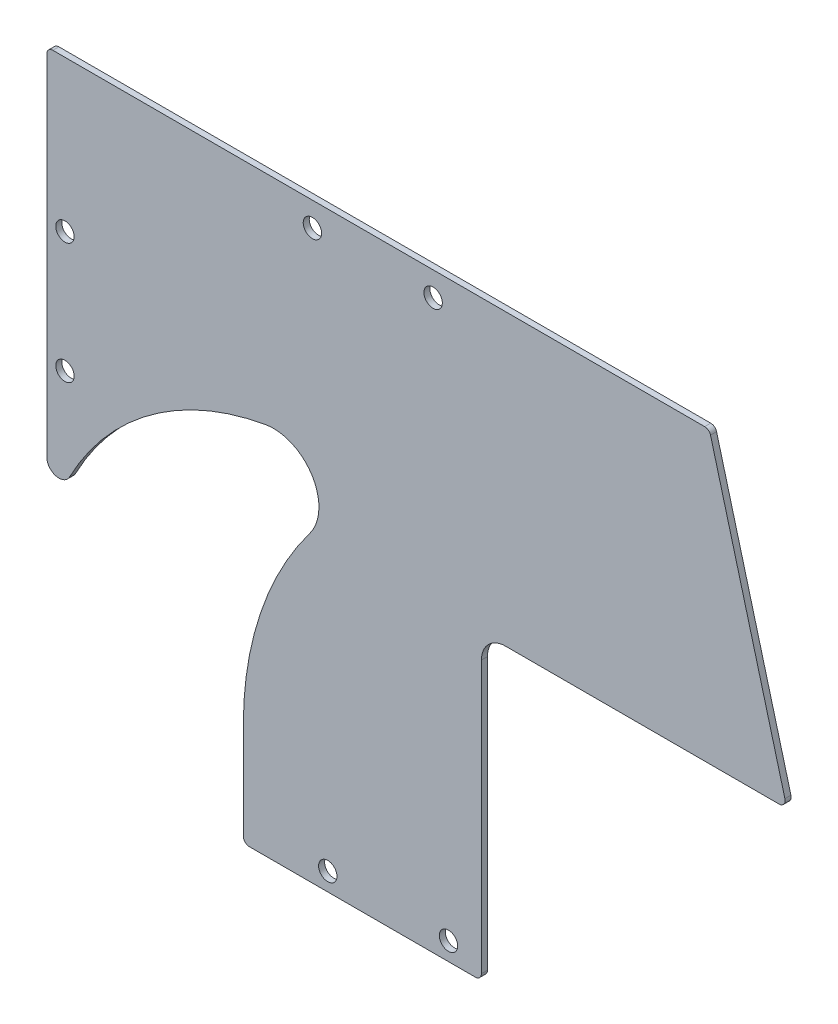
SolidWorks part; units mm, degrees
material "Thornel Mat VMA"
ref_plane "前视基准面" through (0, 0, 0) normal (0, 0, 1) x (1, 0, 0)
ref_plane "上视基准面" through (0, 0, 0) normal (0, 1, 0) x (1, 0, 0)
ref_plane "右视基准面" through (0, 0, 0) normal (1, 0, 0) x (0, 0, -1)
other "Configuration Table"
sketch "草图1" plane through (0, 0, 0) normal (0, 0, 1) x (1, 0, 0)
  line L1 (-70, -51.5) -> (70, -51.5)
  line L2 (-70, -51.5) -> (-70, 51.5)
  line L3 (-70, 51.5) -> (70, 51.5)
  line L4 (70, -51.5) -> (70, 51.5)
  line L5 (-70, -51.5) -> (70, 51.5) construction
  line L6 (-70, 51.5) -> (70, -51.5) construction
  point P0 (0, 0)
  dimension "D1" = 103
  dimension "D2" = 140
extrude "凸台-拉伸1" add sketch "草图1" along normal mid plane 1
sketch "草图2" plane through (0, 0, 0.5) normal (0, 0, 1) x (1, 0, 0)
  line L0 (58.9835, -20.2244) -> (45.4361, 30.3352) construction
  line L1 (67.3638, -51.5) -> (45.4361, 30.3352) construction
  line L2 (-70, -51.5) -> (70, -51.5) construction
  line L3 (-68.4454, -29.5) -> (-68.4454, -77.5)
  line L4 (-66.4454, -79.5) -> (-42.4454, -79.5)
  line L5 (-40.4454, -77.5) -> (-40.4454, -29.5)
  line L6 (-68.4454, -29.5) -> (-68.4454, -77.5) construction
  line L7 (-66.4454, -79.5) -> (-42.4454, -79.5) construction
  line L8 (-40.4454, -77.5) -> (-40.4454, -29.5) construction
  line L9 (-71.4454, -29.5) -> (-71.4454, -77.5)
  line L10 (6, -79.5) -> (34, -79.5)
  line L11 (35, -78.5) -> (35, -0.5)
  line L12 (34, 0.5) -> (6, 0.5)
  line L13 (5, -0.5) -> (5, -78.5)
  line L14 (6, -79.5) -> (34, -79.5) construction
  line L15 (35, -78.5) -> (35, -0.5) construction
  line L16 (34, 0.5) -> (6, 0.5) construction
  line L17 (5, -0.5) -> (5, -78.5) construction
  line L18 (-66.4454, -82.5) -> (-42.4454, -82.5)
  line L19 (-37.4454, -77.5) -> (-37.4454, -29.5)
  line L20 (6, -82.5) -> (34, -82.5)
  line L21 (38, -78.5) -> (38, -0.5)
  line L22 (34, 3.5) -> (6, 3.5)
  line L23 (2, -0.5) -> (2, -78.5)
  arc A0 (-71.4454, -77.5) -> (-66.4454, -82.5) centre (-66.4454, -77.5) ccw
  arc A1 (-42.4454, -82.5) -> (-37.4454, -77.5) centre (-42.4454, -77.5) ccw
  arc A2 (-26.4309, 3.4778) -> (-37.4454, -29.5) centre (17.4298, -29.5) ccw
  arc A3 (-26.4309, 3.4778) -> (-33.7501, 15.411) centre (-32.4454, 8) ccw
  arc A4 (34, -79.5) -> (35, -78.5) centre (34, -78.5) ccw
  arc A5 (-68.4454, -77.5) -> (-66.4454, -79.5) centre (-66.4454, -77.5) ccw
  arc A6 (-42.4454, -79.5) -> (-40.4454, -77.5) centre (-42.4454, -77.5) ccw
  arc A7 (-28.8287, 5.2807) -> (-40.4454, -29.5) centre (17.4298, -29.5) ccw
  arc A8 (-28.8287, 5.2807) -> (-33.23, 12.4565) centre (-32.4454, 8) ccw
  arc A9 (-33.23, 12.4565) -> (-68.4454, -29.5) centre (-25.8438, -29.5) ccw
  arc A10 (-68.4454, -77.5) -> (-66.4454, -79.5) centre (-66.4454, -77.5) ccw construction
  arc A11 (-42.4454, -79.5) -> (-40.4454, -77.5) centre (-42.4454, -77.5) ccw construction
  arc A12 (-28.8287, 5.2807) -> (-40.4454, -29.5) centre (17.4298, -29.5) ccw construction
  arc A13 (-28.8287, 5.2807) -> (-33.23, 12.4565) centre (-32.4454, 8) ccw construction
  arc A14 (-33.23, 12.4565) -> (-68.4454, -29.5) centre (-25.8438, -29.5) ccw construction
  arc A15 (35, -0.5) -> (34, 0.5) centre (34, -0.5) ccw
  arc A16 (6, 0.5) -> (5, -0.5) centre (6, -0.5) ccw
  arc A17 (5, -78.5) -> (6, -79.5) centre (6, -78.5) ccw
  arc A18 (34, -79.5) -> (35, -78.5) centre (34, -78.5) ccw construction
  arc A19 (35, -0.5) -> (34, 0.5) centre (34, -0.5) ccw construction
  arc A20 (6, 0.5) -> (5, -0.5) centre (6, -0.5) ccw construction
  arc A21 (5, -78.5) -> (6, -79.5) centre (6, -78.5) ccw construction
  arc A22 (-33.7501, 15.411) -> (-71.4454, -29.5) centre (-25.8438, -29.5) ccw
  arc A23 (34, -82.5) -> (38, -78.5) centre (34, -78.5) ccw
  arc A24 (38, -0.5) -> (34, 3.5) centre (34, -0.5) ccw
  arc A25 (6, 3.5) -> (2, -0.5) centre (6, -0.5) ccw
  arc A26 (2, -78.5) -> (6, -82.5) centre (6, -78.5) ccw
  dimension "D1" = 0
  dimension "D2" = 0
  dimension "D3" = 3
  dimension "D4" = 3
extrude "切除-拉伸1" cut sketch "草图2" against normal mid plane 3
sketch "草图3" plane through (0, 0, 0.5) normal (0, 0, 1) x (1, 0, 0)
  line L0 (67.3638, -51.5) -> (39.765, 51.5)
  line L1 (70, 51.5) -> (-70, 51.5) construction
  line L2 (39.765, 51.5) -> (70, 51.5)
  line L3 (70, 51.5) -> (70, -51.5)
  line L4 (70, -51.5) -> (67.3638, -51.5)
  line L5 (67.3638, -51.5) -> (45.4361, 30.3352) construction
extrude "切除-拉伸2" cut sketch "草图3" against normal mid plane 3
sketch "草图4" plane through (0, 0, 0.5) normal (0, 0, 1) x (1, 0, 0)
  line L1 (34, 3.5) -> (67.3638, 3.5)
  line L2 (34, 3.5) -> (34, -51.5)
  line L3 (34, -51.5) -> (67.3638, -51.5)
  line L4 (67.3638, 3.5) -> (67.3638, -51.5)
extrude "切除-拉伸3" cut sketch "草图4" against normal mid plane 2
fillet "圆角1" radius 2 1 edges at (-70, -18.1096, 0)
sketch "草图5" plane through (0, 0, 0.5) normal (0, 0, 1) x (1, 0, 0)
  line L0 (-70, 51.5) -> (-70, -7.3918) construction
  line L1 (-77, 2.0541) -> (-63, 2.0541)
  line L2 (-77, 2.0541) -> (-77, 42.0541)
  line L3 (-77, 42.0541) -> (-63, 42.0541)
  line L4 (-63, 2.0541) -> (-63, 42.0541)
  line L5 (-77, 2.0541) -> (-63, 42.0541) construction
  line L6 (-77, 42.0541) -> (-63, 2.0541) construction
  point P0 (-70, 22.0541)
  dimension "D1" = 40
  dimension "D2" = 7
extrude "凸台-拉伸2" [suppressed] add sketch "草图5" against normal up to surface (1 mm away)
sketch "草图6" plane through (0, 0, 0.5) normal (0, 0, 1) x (1, 0, 0)
  circle A0 centre (-26, 47.5) radius 1.25 construction
  circle A1 centre (-6, 47.5) radius 1.25 construction
  circle A2 centre (-26, 47.5) radius 1.25 construction
  circle A3 centre (-6, 47.5) radius 1.25 construction
  circle A4 centre (-26, 47.5) radius 1.525
  circle A5 centre (-6, 47.5) radius 1.25 construction
  circle A6 centre (-6, 47.5) radius 1.525
  dimension "D1" = 3.05
extrude "切除-拉伸5" cut sketch "草图6" against normal blind 10
sketch "草图7" plane through (0, 0, -0.5) normal (0, 0, -1) x (-1, 0, 0)
  circle A0 centre (67, 26.5) radius 1.25 construction
  circle A1 centre (67, 6.5) radius 1.25 construction
  circle A2 centre (67, 26.5) radius 1.25 construction
  circle A3 centre (67, 6.5) radius 1.25 construction
  circle A4 centre (67, 6.5) radius 1.525
  circle A5 centre (67, 26.5) radius 1.525
  dimension "D1" = 3.05
extrude "切除-拉伸6" cut sketch "草图7" against normal blind 10
sketch "草图8" plane through (0, 0, 0.5) normal (0, 0, 1) x (1, 0, 0)
  line L0 (-37.4454, -46.5) -> (2, -46.5)
  line L1 (-37.4454, -29.5) -> (-37.4454, -51.5) construction
  line L2 (2, -51.5) -> (2, -0.5) construction
  line L3 (2, -46.5) -> (2, -51.5)
  line L4 (2, -51.5) -> (-37.4454, -51.5)
  line L5 (-37.4454, -51.5) -> (-37.4454, -46.5)
  circle A0 centre (-23.45, -43.5) radius 1.525 construction
  circle A1 centre (-3.45, -43.5) radius 1.525 construction
  circle A2 centre (-23.45, -43.5) radius 1.525 construction
  circle A3 centre (-3.45, -43.5) radius 1.525 construction
  circle A4 centre (-23.45, -43.5) radius 1.525
  circle A5 centre (-3.45, -43.5) radius 1.525
  dimension "D1" = 3.05
  dimension "D2" = 3
extrude "切除-拉伸7" cut sketch "草图8" against normal blind 10
fillet "圆角2" radius 1 5 edges at (52.6266, 3.5, 0) (39.765, 51.5, 0) (-70, 51.5, 0) (2, -46.5, 0) (-37.4454, -46.5, 0)
